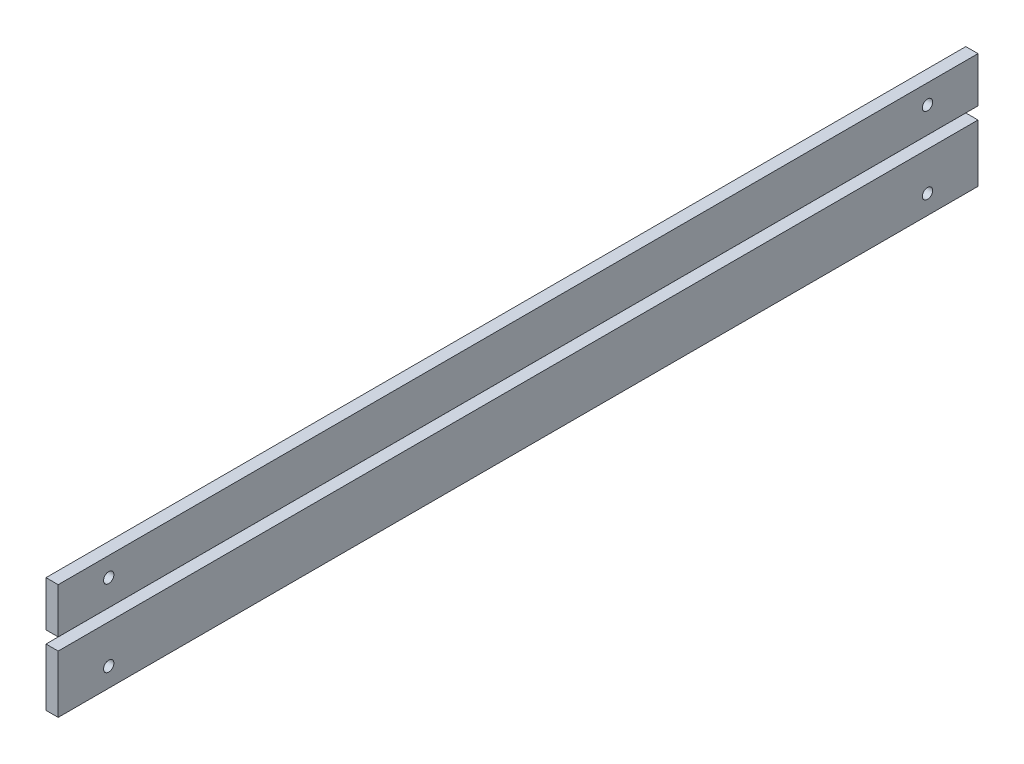
SolidWorks part; units mm, degrees
ref_plane "Front Plane" through (0, 0, 0) normal (0, 0, 1) x (1, 0, 0)
ref_plane "Top Plane" through (0, 0, 0) normal (0, 1, 0) x (1, 0, 0)
ref_plane "Right Plane" through (0, 0, 0) normal (1, 0, 0) x (0, 0, -1)
sketch "Sketch1" plane through (0, 0, 0) normal (1, 0, 0) x (0, 0, -1)
  line L1 (-120, 15) -> (120, 15)
  line L2 (-120, 15) -> (-120, -15)
  line L3 (-120, -15) -> (120, -15)
  line L4 (120, 15) -> (120, -15)
  line L5 (-120, 15) -> (120, -15) construction
  line L6 (-120, -15) -> (120, 15) construction
  point P0 (0, 0)
  dimension "D1" = 30
  dimension "D2" = 240
extrude "Boss-Extrude1" add sketch "Sketch1" along normal blind 3.18
sketch "Sketch2" plane through (0, 0, 0) normal (-1, 0, 0) x (0, 0, 1)
  line L0 (-120, 0) -> (0, 0) construction
  line L1 (-120, -15) -> (-120, 15) construction
  line L2 (0, 0) -> (0, 15) construction
  line L3 (-120, 15) -> (120, 15) construction
  line L4 (0, 7.5) -> (-120, 7.5) construction
  line L5 (-106.82, 10) -> (-106.82, 5) construction
  circle A0 centre (-106.82, 10) radius 1.35
  point P14 (-106.82, 7.5)
  dimension "D1" = 2.7
  dimension "D2" = 5
  dimension "D3" = 13.18
extrude "Cut-Extrude1" cut sketch "Sketch2" against normal up to next
mirror "Mirror1" about plane through (0, 0, 0) normal (0, 1, 0) of "Cut-Extrude1"
mirror "Mirror2" about plane through (0, 0, 0) normal (0, 0, 1) of "Mirror1", "Cut-Extrude1"
sketch "Sketch3" plane through (3.18, 0, 0) normal (1, 0, 0) x (0, 0, -1)
  line L1 (-120, 0) -> (120, 0)
  line L2 (-120, 0) -> (-120, 3.19)
  line L3 (-120, 3.19) -> (120, 3.19)
  line L4 (120, 0) -> (120, 3.19)
  dimension "D1" = 3.19
  dimension "D2" = 240
extrude "Cut-Extrude2" cut sketch "Sketch3" against normal blind 10
